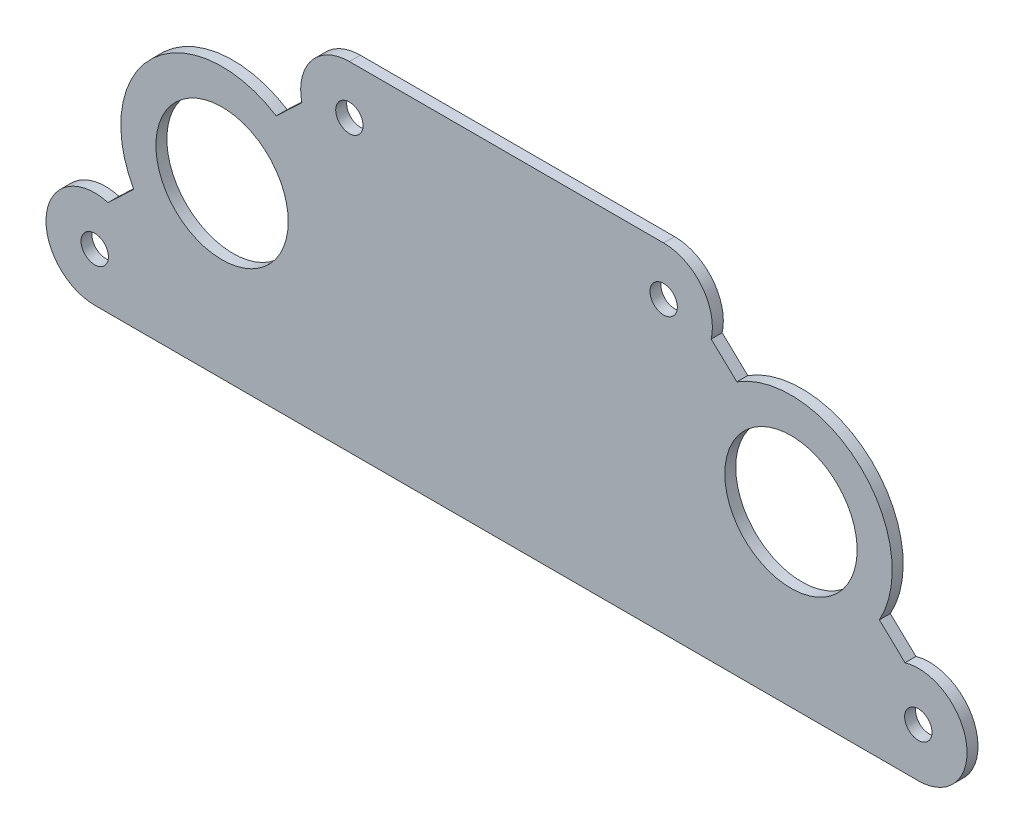
SolidWorks part; units mm, degrees
material "6061 Alloy"
ref_plane "Front Plane" through (0, 0, 0) normal (0, 0, 1) x (1, 0, 0)
ref_plane "Top Plane" through (0, 0, 0) normal (0, 1, 0) x (1, 0, 0)
ref_plane "Right Plane" through (0, 0, 0) normal (1, 0, 0) x (0, 0, -1)
sketch "Sketch1" plane through (0, 0, 0) normal (0, 0, 1) x (1, 0, 0)
  line L0 (-156.7798, 13.5446) -> (-37.4492, 13.5446)
  line L1 (-39.3761, 27.399) -> (-43.0906, 30.9139)
  line L2 (-119.881, 62.5829) -> (-74.348, 62.5829)
  line L3 (-130.4847, 50.4577) -> (-126.7702, 53.9726)
  line L4 (-63.7443, 50.4577) -> (-67.4588, 53.9726)
  line L5 (-154.8529, 27.399) -> (-151.1384, 30.9139)
  line L13 (-97.1145, 13.5446) -> (-97.1145, -114.9643) construction
  arc A0 (-154.8529, 27.399) -> (-156.7798, 13.5446) centre (-156.7798, 20.6058) ccw
  circle A1 centre (-37.4492, 20.6058) radius 1.9812
  circle A2 centre (-138.3304, 38.0637) radius 9.5885
  arc A3 (-39.3761, 27.399) -> (-37.4492, 13.5446) centre (-37.4492, 20.6058) cw
  circle A4 centre (-119.881, 55.5217) radius 1.9812
  circle A5 centre (-156.7798, 20.6058) radius 1.9812
  arc A6 (-119.881, 62.5829) -> (-126.7702, 53.9726) centre (-119.881, 55.5217) ccw
  arc A8 (-130.4847, 50.4577) -> (-151.1384, 30.9139) centre (-138.3304, 38.0637) ccw
  circle A9 centre (-74.348, 55.5217) radius 1.9812
  arc A10 (-74.348, 62.5829) -> (-67.4588, 53.9726) centre (-74.348, 55.5217) cw
  arc A11 (-63.7443, 50.4577) -> (-43.0906, 30.9139) centre (-55.8986, 38.0637) cw
  circle A12 centre (-55.8986, 38.0637) radius 9.5885
  point P19 (-97.1145, 62.5829)
  dimension "D2" = 5.08
  dimension "D15" = 50.8
  dimension "D9" = 3.9624
  dimension "D4" = 19.177
  dimension "D10" = 3.9624
  dimension "D12" = 25.4
  dimension "D14" = 25.4
  dimension "D6" = 5.08
extrude "Boss-Extrude1" add sketch "Sketch1" along normal blind 1.5875
